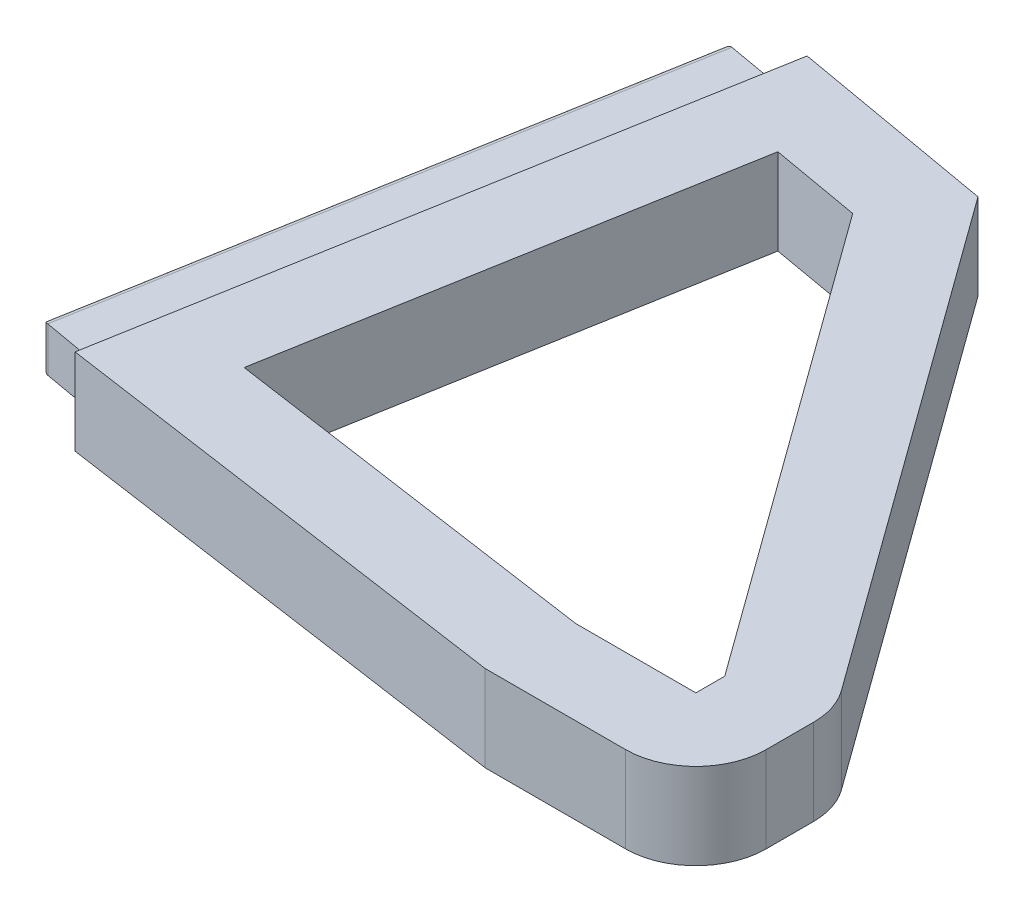
SolidWorks part; units mm, degrees
ref_plane "Front Plane" through (0, 0, 0) normal (0, 0, 1) x (1, 0, 0)
ref_plane "Top Plane" through (0, 0, 0) normal (0, 1, 0) x (1, 0, 0)
ref_plane "Right Plane" through (0, 0, 0) normal (1, 0, 0) x (0, 0, -1)
sketch "Sketch1" plane through (0, 0, 0) normal (0, 1, 0) x (1, 0, 0)
  line L0 (0, 0) -> (1.7365, 9.8481) construction
  line L1 (17.3648, 98.4808) -> (46.9091, 93.2713)
  line L2 (46.9091, 93.2713) -> (98.0977, 22.6254)
  line L3 (100, 16.7579) -> (100, 10)
  line L4 (90, 0) -> (70, 0)
  line L5 (70, 0) -> (1.7365, 9.8481)
  line L6 (40.0418, 82.2971) -> (88, 16.1095)
  line L7 (88, 16.1095) -> (88, 12)
  line L8 (88, 12) -> (70.8611, 12)
  line L9 (70.8611, 12) -> (15.7041, 19.9573)
  line L10 (27.0987, 84.5793) -> (15.7041, 19.9573)
  line L11 (27.0987, 84.5793) -> (40.0418, 82.2971)
  line L13 (17.3648, 98.4808) -> (1.7365, 9.8481)
  line L14 (0, 0) -> (0, 85.2296) construction
  line L15 (0, 0) -> (100, 0) construction
  line L16 (100, 0) -> (99.8638, -0.0847) construction
  arc A0 (98.0977, 22.6254) -> (100, 16.7579) centre (90, 16.7579) cw
  arc A1 (100, 10) -> (90, 0) centre (90, 10) cw
  arc A2 (88, 16.1095) -> (88, 16.1095) centre (88, 16.1095) cw
  arc A3 (88, 12) -> (88, 12) centre (88, 12) cw
  point P19 (100, 20)
  dimension "D9" = 10
  dimension "D1" = 90
  dimension "D2" = 10
  dimension "D3" = 30
  dimension "D4" = 10
  dimension "D5" = 20
  dimension "D6" = 100
  dimension "D8" = 30
  dimension "D7" = 12
extrude "Boss-Extrude1" add sketch "Sketch1" along normal blind 12.25
sketch "Sketch2" plane through (0, 0, 0) normal (-0.9848, 0, -0.1736) x (-0.1736, 0, 0.9848)
  line L14 (-12.95, 2.95) -> (-12.95, 9.3)
  line L15 (-97.05, 2.95) -> (-12.95, 2.95)
  line L16 (-97.05, 9.3) -> (-97.05, 2.95)
  line L17 (-12.95, 9.3) -> (-97.05, 9.3)
  line L18 (-12.95, 2.95) -> (-12.95, 9.3)
  line L19 (-97.05, 2.95) -> (-12.95, 2.95)
  line L20 (-97.05, 9.3) -> (-97.05, 2.95)
  line L21 (-12.95, 9.3) -> (-97.05, 9.3)
  dimension "D1" = 2.95
extrude "Boss-Extrude2" add sketch "Sketch2" along normal blind 10
fillet "Fillet1" radius 1 4 edges at (-7.5993, 6.125, -14.4897) (-0.2974, 2.95, -55.9009) (7.0045, 6.125, -97.3121) (-0.2974, 9.3, -55.9009)
